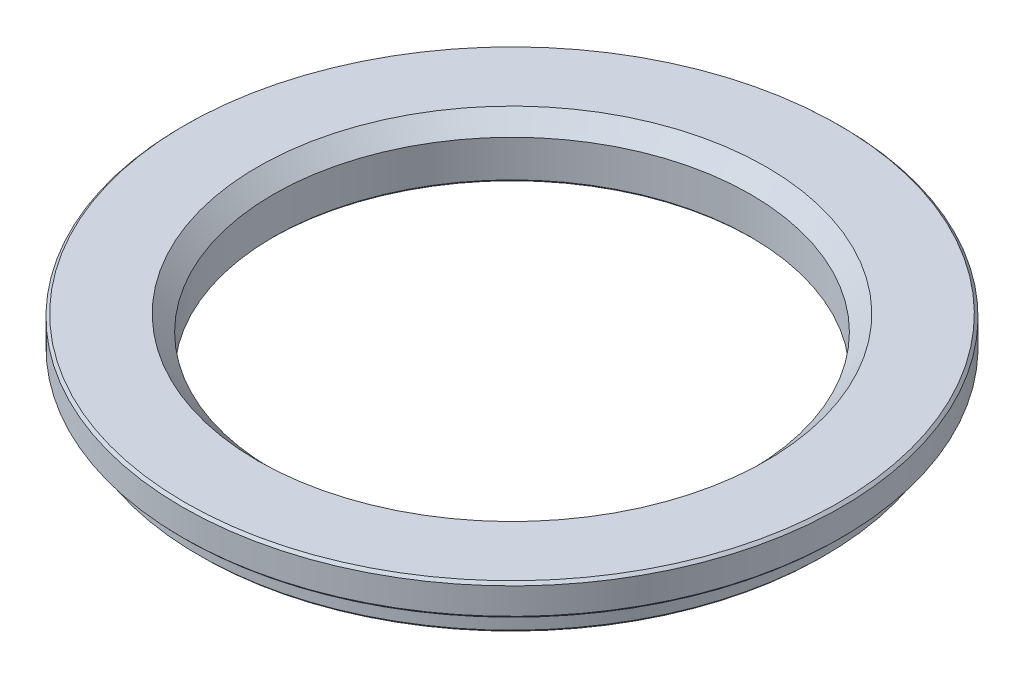
SolidWorks part; units mm, degrees
ref_plane "Plano frontal" through (0, 0, 0) normal (0, 0, 1) x (1, 0, 0)
ref_plane "Plano superior" through (0, 0, 0) normal (0, 1, 0) x (1, 0, 0)
ref_plane "Plano direito" through (0, 0, 0) normal (1, 0, 0) x (0, 0, -1)
sketch "Esboço1" plane through (0, 0, 0) normal (0, 0, 1) x (1, 0, 0)
  line L0 (0, -46.0252) -> (0, 52.0025) construction
  line L1 (45.25, 9.4441) -> (62.5, 9.4441)
  line L2 (62.5, 9.4441) -> (62.5, 3.4441)
  line L3 (62.5, 3.4441) -> (59.3564, 3.4441)
  line L4 (59.3564, 3.4441) -> (59.3564, -1.0559)
  line L5 (59.3564, -1.0559) -> (45.25, -1.0559)
  line L6 (45.25, -1.0559) -> (45.25, 9.4441)
  dimension "D1" = 62.5
  dimension "D2" = 45.25
  dimension "D3" = 10.5
  dimension "D4" = 4.5
revolve "Revolução1" add sketch "Esboço1" angle 360 about L0
chamfer "Chanfro1" distance 3 angle 45 1 edges at (0, 9.4441, -45.25)
chamfer "Chanfro2" distance 0.5 angle 45 4 edges at (0, -1.0559, -59.3564) (0, 3.4441, -62.5) (0, 9.4441, -62.5) (0, -1.0559, -45.25)
